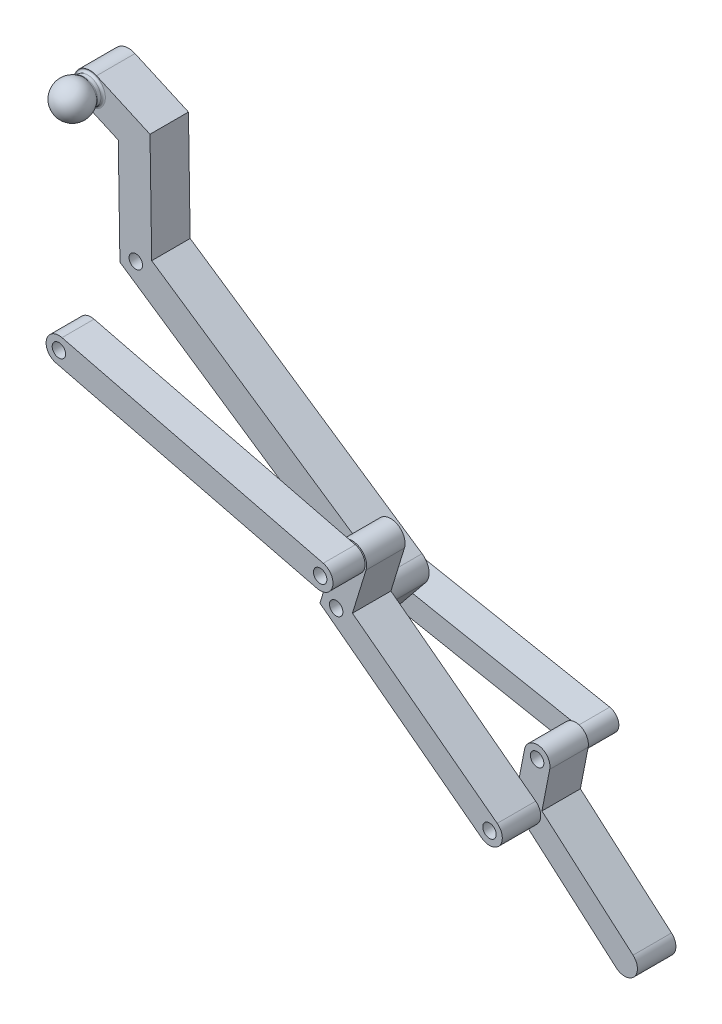
SolidWorks part; units mm, degrees
ref_plane "Plan de face" through (0, 0, 0) normal (0, 0, 1) x (1, 0, 0)
ref_plane "Plan de dessus" through (0, 0, 0) normal (0, 1, 0) x (1, 0, 0)
ref_plane "Plan de droite" through (0, 0, 0) normal (1, 0, 0) x (0, 0, -1)
sketch "Mouvement-Relation" plane through (0, 0, 0) normal (0, 0, 1) x (1, 0, 0)
  line L0 (0, 0) -> (20, 0)
  line L1 (20, 3) -> (57.2643, -22.2264)
  line L2 (20, 3) -> (12.8508, 22.7456) construction
  line L3 (20, 0) -> (20, -4) construction
  line L4 (20, -4) -> (19, -4) construction
  line L5 (19, -4) -> (59.7667, -14.1032) construction
  line L6 (57.2643, -22.2264) -> (59.7667, -14.1032) construction
  line L7 (57.2643, -22.2264) -> (81.1849, -40.3318)
  line L8 (53.1652, -27.271) -> (82.6189, -32.9702) construction
  line L9 (57.2643, -22.2264) -> (53.1652, -27.271) construction
  line L10 (81.1849, -40.3318) -> (96.2738, -53.459)
  line L11 (81.1849, -40.3318) -> (82.6189, -32.9702) construction
  line L12 (20, 3) -> (20, 0)
  circle A1 centre (20, 3) radius 21 construction
  circle A2 centre (57.2643, -22.2264) radius 8.5 construction
  circle A3 centre (81.1849, -40.3318) radius 7.5 construction
  circle A4 centre (57.2643, -22.2264) radius 6.5 construction
  dimension "D3" = 42
  dimension "D6" = 17
  dimension "D12" = 15
  dimension "D17" = 13
  dimension "D1" = 20
  dimension "D2" = 3
  dimension "D4" = 144
  dimension "D5" = 4
  dimension "D7" = 1
  dimension "D8" = 110
  dimension "D9" = 30
  dimension "D10" = 20
  dimension "D11" = 120
  dimension "D13" = 85
  dimension "D15" = 45
  dimension "D14" = 30
  dimension "D16" = 42
sketch "Esquisse6" plane through (0, 0, 0) normal (0, 0, 1) x (1, 0, 0)
  line L0 (17.5208, 1.6593) -> (53.6035, -22.7672)
  line L4 (22.4792, 4.3407) -> (58.6658, -20.1562)
  line L5 (59.2045, -23.803) -> (55.1054, -28.8476)
  line L6 (51.225, -25.6944) -> (53.6035, -22.7672)
  line L7 (20, 3) -> (57.2643, -22.2264) construction
  line L8 (57.2643, -22.2264) -> (53.1652, -27.271) construction
  line L9 (13.8715, 25.0278) -> (22.2117, 21.2976)
  line L10 (22.2117, 21.2976) -> (22.4792, 4.3407)
  line L11 (17.5208, 1.6593) -> (17.2626, 18.0338)
  line L12 (17.2626, 18.0338) -> (11.8301, 20.4635)
  arc A1 (11.8301, 20.4635) -> (13.8715, 25.0278) centre (12.8508, 22.7456) cw
  arc A2 (58.6658, -20.1562) -> (59.2045, -23.803) centre (57.2643, -22.2264) cw
  arc A3 (55.1054, -28.8476) -> (51.225, -25.6944) centre (53.1652, -27.271) cw
  circle A4 centre (20, 3) radius 2.5 construction
  dimension "D2" = 2.5
  dimension "D1" = 5
  dimension "D3" = 5
  dimension "D4" = 5
  dimension "D5" = 125
  dimension "D6" = 115
extrude "Boss.-Extru.1" add sketch "Esquisse6" against normal blind 6
sketch "Esquisse7" plane through (0, 0, 0) normal (0, 0, 1) x (1, 0, 0)
  line L0 (54.7285, -22.8154) -> (57.6164, -13.4407)
  line L1 (61.917, -14.7656) -> (59.8001, -21.6375)
  line L2 (59.8001, -21.6375) -> (82.3919, -38.7371)
  line L3 (79.9779, -41.9265) -> (54.7285, -22.8154)
  line L4 (57.2643, -22.2264) -> (81.1849, -40.3318) construction
  line L5 (57.2643, -22.2264) -> (59.7667, -14.1032) construction
  arc A0 (57.6164, -13.4407) -> (61.917, -14.7656) centre (59.7667, -14.1032) cw
  arc A1 (82.3919, -38.7371) -> (79.9779, -41.9265) centre (81.1849, -40.3318) cw
  dimension "D1" = 4
  dimension "D2" = 4.5
extrude "Boss.-Extru.2" add sketch "Esquisse7" along normal blind 6 separate body
sketch "Esquisse8" plane through (0, 0, 0) normal (0, 0, 1) x (1, 0, 0)
  line L0 (79.001, -41.0828) -> (94.9611, -54.9679)
  line L1 (97.5866, -51.9501) -> (83.3688, -39.5808)
  line L2 (83.3688, -39.5808) -> (84.582, -33.3526)
  line L3 (80.6558, -32.5878) -> (79.001, -41.0828)
  line L4 (81.1849, -40.3318) -> (96.2738, -53.459) construction
  line L5 (81.1849, -40.3318) -> (82.6189, -32.9702) construction
  arc A0 (94.9611, -54.9679) -> (97.5866, -51.9501) centre (96.2738, -53.459) ccw
  arc A1 (84.582, -33.3526) -> (80.6558, -32.5878) centre (82.6189, -32.9702) ccw
  dimension "D1" = 4
  dimension "D2" = 4
extrude "Boss.-Extru.3" add sketch "Esquisse8" against normal blind 6 separate body
sketch "Esquisse9" plane through (0, 0, 0) normal (0, 0, 1) x (1, 0, 0)
  line L0 (19, -4) -> (59.7667, -14.1032) construction
  line L1 (19.4811, -2.0587) -> (60.2478, -12.1619)
  line L2 (18.5189, -5.9413) -> (59.2856, -16.0444)
  arc A0 (19.4811, -2.0587) -> (18.5189, -5.9413) centre (19, -4) ccw
  arc A1 (59.2856, -16.0444) -> (60.2478, -12.1619) centre (59.7667, -14.1032) ccw
  point P6 (39.3834, -9.0516)
  dimension "D1" = 4
extrude "Boss.-Extru.4" add sketch "Esquisse9" along normal blind 5 from offset 6 separate body
sketch "Esquisse10" plane through (0, 0, 0) normal (0, 0, 1) x (1, 0, 0)
  line L0 (53.1652, -27.271) -> (82.6189, -32.9702) construction
  line L1 (53.4977, -25.5529) -> (82.9513, -31.2521)
  line L2 (52.8327, -28.9891) -> (82.2864, -34.6883)
  arc A0 (53.4977, -25.5529) -> (52.8327, -28.9891) centre (53.1652, -27.271) ccw
  arc A1 (82.2864, -34.6883) -> (82.9513, -31.2521) centre (82.6189, -32.9702) ccw
  point P6 (67.892, -30.1206)
  dimension "D1" = 3.5
extrude "Boss.-Extru.5" add sketch "Esquisse10" against normal blind 5 from offset 6 separate body contours L1 A1 L2 A0 offset against normal yes
sketch "Esquisse13" plane through (0, 0, 0) normal (0, 0, 1) x (1, 0, 0)
  circle A1 centre (20, 3) radius 1.05
  circle A2 centre (19, -4) radius 1.05
  circle A3 centre (59.7667, -14.1032) radius 1.05
  circle A4 centre (57.2643, -22.2264) radius 1.05
  circle A5 centre (53.1652, -27.271) radius 1.05
  circle A6 centre (82.6189, -32.9702) radius 1.05
  circle A7 centre (81.1849, -40.3318) radius 1.05
  dimension "D1" = 2.1
extrude "Enlèv. mat.-Extru.1" cut sketch "Esquisse13" against normal through all both and the other way through all
sketch "Esquisse14" plane through (0, 0, 0) normal (0, 0, 1) x (1, 0, 0)
  line L1 (17.5208, 1.6593) -> (53.6035, -22.7672) construction
  circle A0 centre (20, 3) radius 2.5
  circle A1 centre (20, 3) radius 1.075
  dimension "D1" = 2.15
sketch "Esquisse18" plane through (0, 0, 0) normal (0, 0, -1) x (-1, 0, 0)
  circle A0 centre (-12.8508, 22.7456) radius 2.05
  dimension "D1" = 4.1
extrude "Boss.-Extru.7" add sketch "Esquisse18" against normal blind 2
ref_axis "Axe1" through (12.8508, 22.7456, 0) along (0, 0, 1)
ref_plane "Plan1" through (12.8508, 0, 0) normal (1, 0, 0) x (0, 0, -1)
sketch "Esquisse19" plane through (12.8508, 0, 0) normal (1, 0, 0) x (0, 0, -1)
  line L0 (-5.45, 22.7456) -> (-0.05, 22.7456)
  line L1 (0, 22.7456) -> (-2, 22.7456) construction
  line L2 (0, 21.2976) -> (0, 25.0278) construction
  arc A0 (-0.05, 22.7456) -> (-5.45, 22.7456) centre (-2.75, 22.7456) ccw
  dimension "D1" = 2.7
  dimension "D2" = 0.05
revolve "Révolution1" add sketch "Esquisse19" angle 360 about axis through (12.8508, 22.7456, 0) along (0, 0, 1)
fillet "Congé1" radius 0.35 2 edges at (14.9008, 22.7456, 0.9929) (10.8008, 22.7456, 0)
equation "\"D14@Mouvement-Relation\"=\"D9@Mouvement-Relation\" "
equation "\"D16@Mouvement-Relation\"=\"D15@Mouvement-Relation\"-3"
